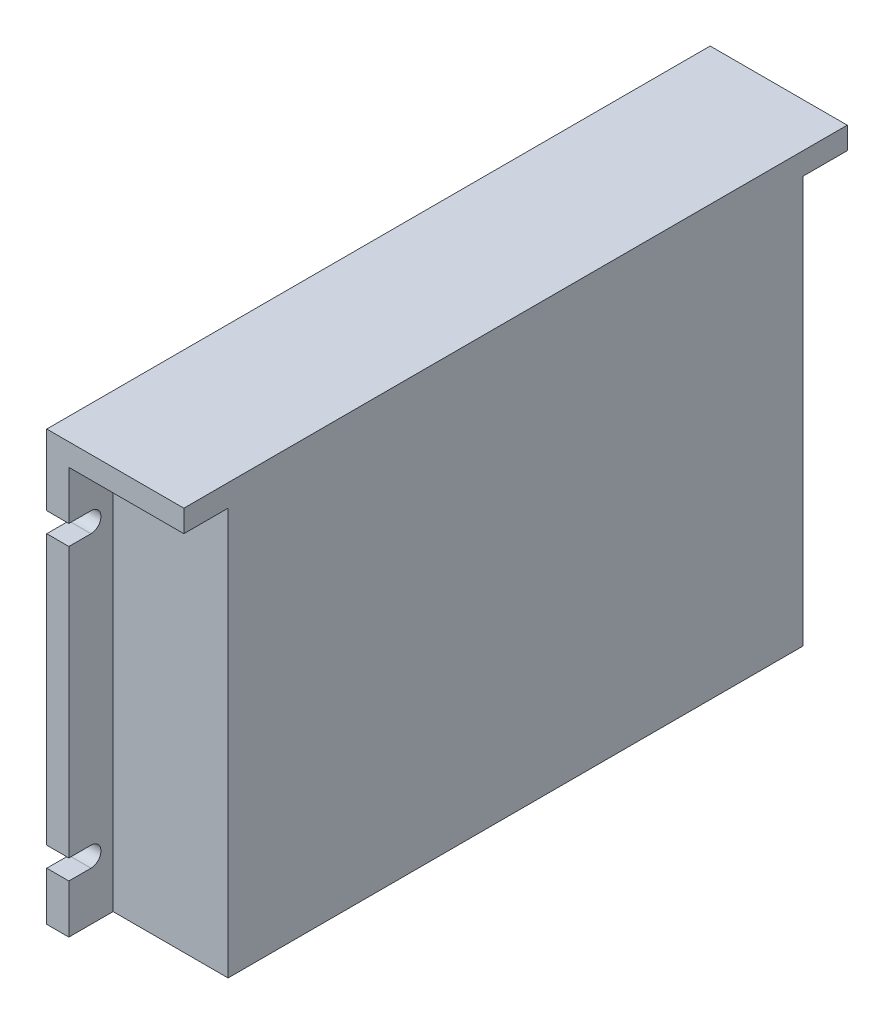
SolidWorks part; units mm, degrees
ref_plane "前视基准面" through (0, 0, 0) normal (0, 0, 1) x (1, 0, 0)
ref_plane "上视基准面" through (0, 0, 0) normal (0, 1, 0) x (1, 0, 0)
ref_plane "右视基准面" through (0, 0, 0) normal (1, 0, 0) x (0, 0, -1)
sketch "草图1" plane through (0, 0, 0) normal (1, 0, 0) x (0, 0, -1)
  line L1 (-75, 48.5) -> (75, 48.5)
  line L2 (-75, 48.5) -> (-75, -48.5)
  line L3 (-75, -48.5) -> (75, -48.5)
  line L4 (75, 48.5) -> (75, -48.5)
  dimension "D1" = 97
  dimension "D2" = 150
  dimension "D3" = 75
  dimension "D4" = 48.5
extrude "凸台-拉伸1" add sketch "草图1" along normal blind 31
sketch "草图2" plane through (31, 0, 0) normal (1, 0, 0) x (0, 0, -1)
  line L0 (75, 48.5) -> (-75, 48.5) construction
  line L1 (-75, -48.5) -> (-65, -48.5)
  line L2 (-75, -48.5) -> (-75, 43.5)
  line L3 (-75, 43.5) -> (-65, 43.5)
  line L4 (-65, -48.5) -> (-65, 43.5)
  line L5 (0, 0) -> (0, 50000) construction
  line L6 (65, -48.5) -> (65, 43.5)
  line L7 (75, 43.5) -> (65, 43.5)
  line L8 (75, -48.5) -> (75, 43.5)
  line L9 (75, -48.5) -> (65, -48.5)
  dimension "D1" = 10
  dimension "D2" = 5
extrude "切除-拉伸1" cut sketch "草图2" against normal blind 26
sketch "草图3" plane through (5, 0, 0) normal (1, 0, 0) x (0, 0, -1)
  line L0 (65, -48.5) -> (75, -48.5) construction
  line L1 (75, -48.5) -> (75, 43.5) construction
  line L2 (-75, 43.5) -> (-75, -48.5) construction
  line L3 (-75, -48.5) -> (-65, -48.5) construction
  line L5 (-70, 32.5) -> (-75, 32.5)
  line L7 (-70, 28) -> (-75, 28)
  line L8 (-75, 32.5) -> (-75, 28)
  line L9 (-70, -33) -> (-75, -33)
  line L11 (-70, -37.5) -> (-75, -37.5)
  line L12 (-75, -33) -> (-75, -37.5)
  circle A0 centre (70, 30.25) radius 2.25
  circle A1 centre (70, -35.25) radius 2.25
  arc A2 (-70, -37.5) -> (-70, -33) centre (-70, -35.25) ccw
  arc A3 (-70, 28) -> (-70, 32.5) centre (-70, 30.25) ccw
  dimension "D1" = 65.5
  dimension "D4" = 4.5
  dimension "D5" = 65.5
  dimension "D6" = 4.5
  dimension "D8" = 13.25
  dimension "D2" = 13.25
  dimension "D3" = 5
  dimension "D7" = 5
extrude "切除-拉伸2" cut sketch "草图3" against normal blind 26
